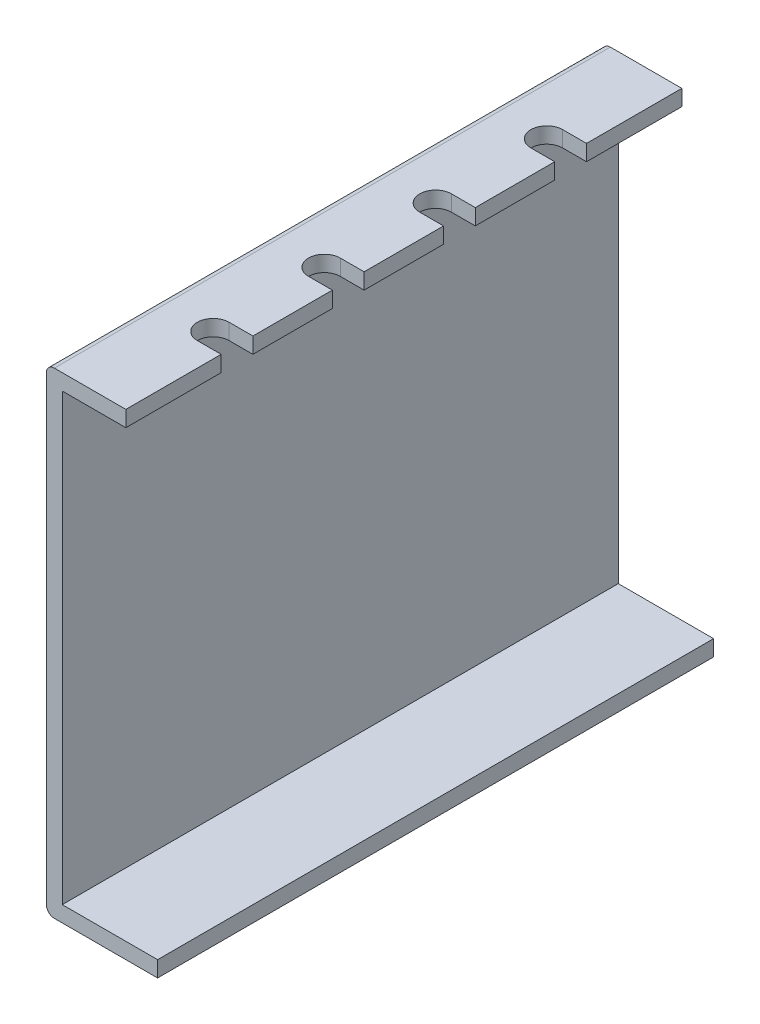
SolidWorks part; units mm, degrees
ref_plane "Front Plane" through (0, 0, 0) normal (0, 0, 1) x (1, 0, 0)
ref_plane "Top Plane" through (0, 0, 0) normal (0, 1, 0) x (1, 0, 0)
ref_plane "Right Plane" through (0, 0, 0) normal (1, 0, 0) x (0, 0, -1)
sketch "Sketch1" plane through (0, 0, 0) normal (0, 0, 1) x (1, 0, 0)
  line L0 (0, 300) -> (0, 0)
  line L1 (0, 0) -> (70, 0)
  line L3 (70, 10) -> (10, 10)
  line L4 (10, 10) -> (10, 290)
  line L5 (10, 290) -> (50, 290)
  line L6 (50, 290) -> (50, 300)
  line L7 (50, 300) -> (0, 300)
  line L11 (70, 10) -> (70, 0)
  dimension "D1" = 300
  dimension "D2" = 10
  dimension "D3" = 10
  dimension "D4" = 10
  dimension "D5" = 70
  dimension "D6" = 50
extrude "Boss-Extrude1" add sketch "Sketch1" along normal mid plane 350
sketch "Sketch2" plane through (0, 300, 0) normal (0, 1, 0) x (1, 0, 0)
  line L1 (35, 115) -> (50, 115)
  line L2 (50, -175) -> (50, 175) construction
  line L3 (35, 95) -> (50, 95)
  line L4 (50, 175) -> (0, 175) construction
  line L5 (50, 115) -> (50, 95)
  arc A0 (35, 115) -> (35, 95) centre (35, 105) ccw
  dimension "D1" = 10
  dimension "D2" = 15
  dimension "D3" = 70
extrude "Cut-Extrude1" cut sketch "Sketch2" against normal up to next
pattern_linear "LPattern1" count 4 spacing 70 along (0, 0, 1) of "Cut-Extrude1"
fillet "Fillet1" radius 5 2 edges at (0, 0, 0) (0, 300, 0)
